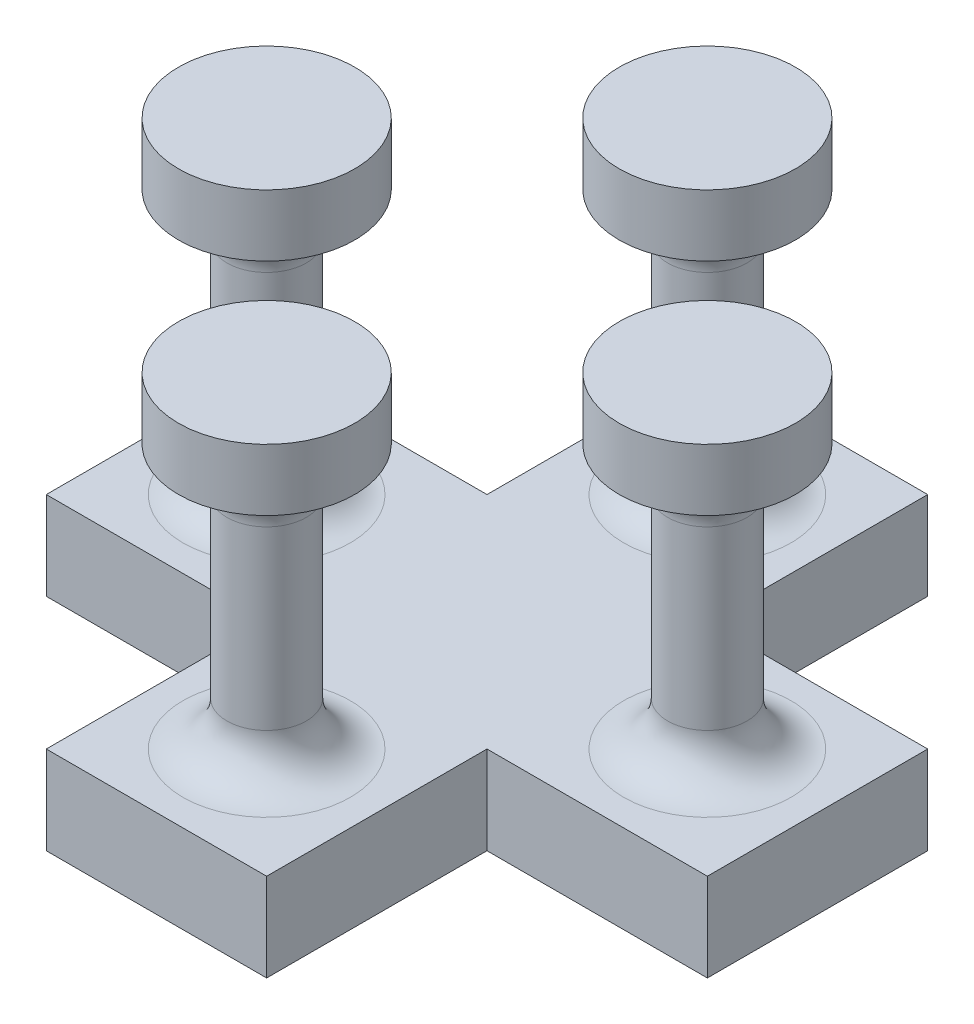
SolidWorks part; units mm, degrees
ref_plane "Front Plane" through (0, 0, 0) normal (0, 0, 1) x (1, 0, 0)
ref_plane "Top Plane" through (0, 0, 0) normal (0, 1, 0) x (1, 0, 0)
ref_plane "Right Plane" through (0, 0, 0) normal (1, 0, 0) x (0, 0, -1)
sketch "Sketch1" plane through (0, 0, 0) normal (0, 1, 0) x (1, 0, 0)
  line L0 (-8.3487, -10.4521) -> (-8.3487, -4.1021)
  line L1 (-8.3487, -4.1021) -> (-1.9987, -4.1021)
  line L2 (-1.9987, -4.1021) -> (-1.9987, -10.4521)
  line L3 (-1.9987, -10.4521) -> (4.3513, -10.4521)
  line L4 (4.3513, -10.4521) -> (4.3513, -16.8021)
  line L5 (4.3513, -16.8021) -> (-1.9987, -16.8021)
  line L6 (-1.9987, -16.8021) -> (-1.9987, -23.1521)
  line L7 (-1.9987, -23.1521) -> (-8.3487, -23.1521)
  line L8 (-8.3487, -23.1521) -> (-8.3487, -16.8021)
  line L9 (-8.3487, -16.8021) -> (-14.6987, -16.8021)
  line L10 (-14.6987, -16.8021) -> (-14.6987, -10.4521)
  line L11 (-14.6987, -10.4521) -> (-8.3487, -10.4521)
  dimension "D1" = 6.35
  dimension "D2" = 6.35
  dimension "D3" = 6.35
  dimension "D4" = 6.35
  dimension "D5" = 6.35
  dimension "D6" = 6.35
  dimension "D7" = 6.35
  dimension "D8" = 6.35
  dimension "D9" = 6.35
  dimension "D10" = 6.35
extrude "body" add sketch "Sketch1" along normal blind 2.54
sketch "Sketch2" plane through (0, 2.54, 0) normal (0, 1, 0) x (1, 0, 0)
  line L0 (-8.3487, -10.4521) -> (-14.6987, -10.4521) construction
  line L1 (-1.9987, -23.1521) -> (-1.9987, -16.8021) construction
  line L2 (-1.9987, -16.8021) -> (4.3513, -16.8021) construction
  line L3 (-1.9987, -10.4521) -> (-1.9987, -4.1021) construction
  line L4 (-1.9987, -4.1021) -> (-8.3487, -4.1021) construction
  line L5 (-14.6987, -10.4521) -> (-14.6987, -16.8021) construction
  line L6 (-8.3487, -23.1521) -> (-1.9987, -23.1521) construction
  line L7 (4.3513, -16.8021) -> (4.3513, -10.4521) construction
  circle A0 centre (-5.1737, -7.2771) radius 1.143
  circle A1 centre (1.1763, -13.6271) radius 1.143
  circle A2 centre (-5.1737, -19.9771) radius 1.143
  circle A3 centre (-11.5237, -13.6271) radius 1.143
  dimension "D1" = 2.286
  dimension "D2" = 2.286
  dimension "D3" = 2.286
  dimension "D4" = 2.286
  dimension "D5" = 3.175
  dimension "D6" = 3.175
  dimension "D7" = 3.175
  dimension "D8" = 3.175
  dimension "D9" = 3.175
  dimension "D10" = 3.175
  dimension "D11" = 3.175
  dimension "D12" = 3.175
extrude "flag" add sketch "Sketch2" along normal blind 7.62
ref_point "centre 1"
ref_point "centre 2"
ref_point "centre 3"
ref_point "centre 4"
ref_plane "plane o' feet" through (0, 10.16, 0) normal (0, 1, 0) x (1, 0, 0)
sketch "Sketch3" plane through (0, 10.16, 0) normal (0, 1, 0) x (1, 0, 0)
  circle A0 centre (-5.1737, -7.2771) radius 2.54
  circle A1 centre (-11.5237, -13.6271) radius 2.54
  circle A2 centre (-5.1737, -19.9771) radius 2.54
  circle A3 centre (1.1763, -13.6271) radius 2.54
  dimension "D1" = 5.08
  dimension "D2" = 5.08
  dimension "D3" = 5.08
  dimension "D4" = 5.08
extrude "feet" add sketch "Sketch3" along normal blind 1.778
fillet "roundness" radius 1.27 8 edges at (-5.1737, 10.16, 8.4201) (-11.5237, 10.16, 14.7701) (-5.1737, 10.16, 21.1201) (1.1763, 10.16, 14.7701) (-11.5237, 2.54, 14.7701) (-5.1737, 2.54, 21.1201) (1.1763, 2.54, 14.7701) (-5.1737, 2.54, 8.4201)
